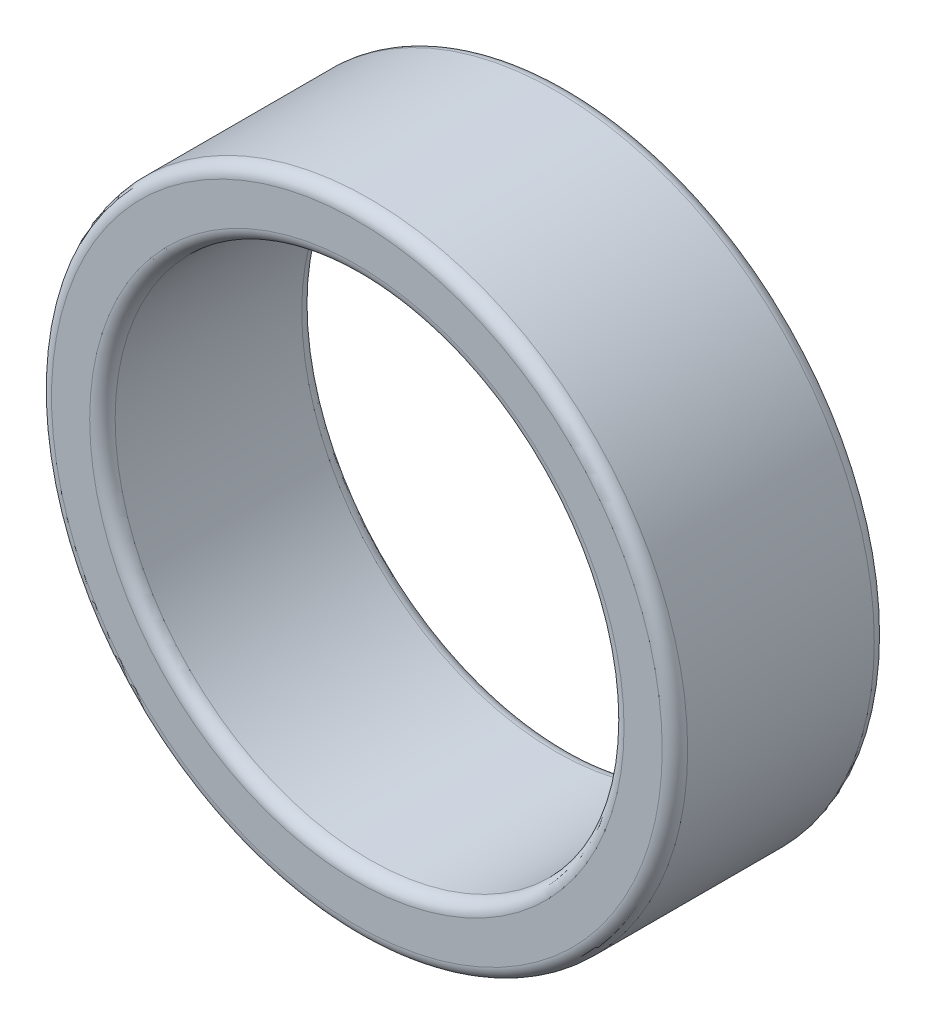
SolidWorks part; units mm, degrees
ref_plane "Front" through (0, 0, 0) normal (0, 0, 1) x (1, 0, 0)
ref_plane "Top" through (0, 0, 0) normal (0, 1, 0) x (1, 0, 0)
ref_plane "Right" through (0, 0, 0) normal (1, 0, 0) x (0, 0, -1)
sketch "Sketch1" plane through (0, 0, 0) normal (0, 0, 1) x (1, 0, 0)
  circle A0 centre (0, 0) radius 6
  circle A1 centre (0, 0) radius 7.5
  dimension "D1" = 12
  dimension "D2" = 15
extrude "Boss-Extrude1" add sketch "Sketch1" against normal blind 5
fillet "Fillet1" radius 0.3 4 edges at (7.5, 0, 0) (7.5, 0, -5) (6, 0, 0) (6, 0, -5)
